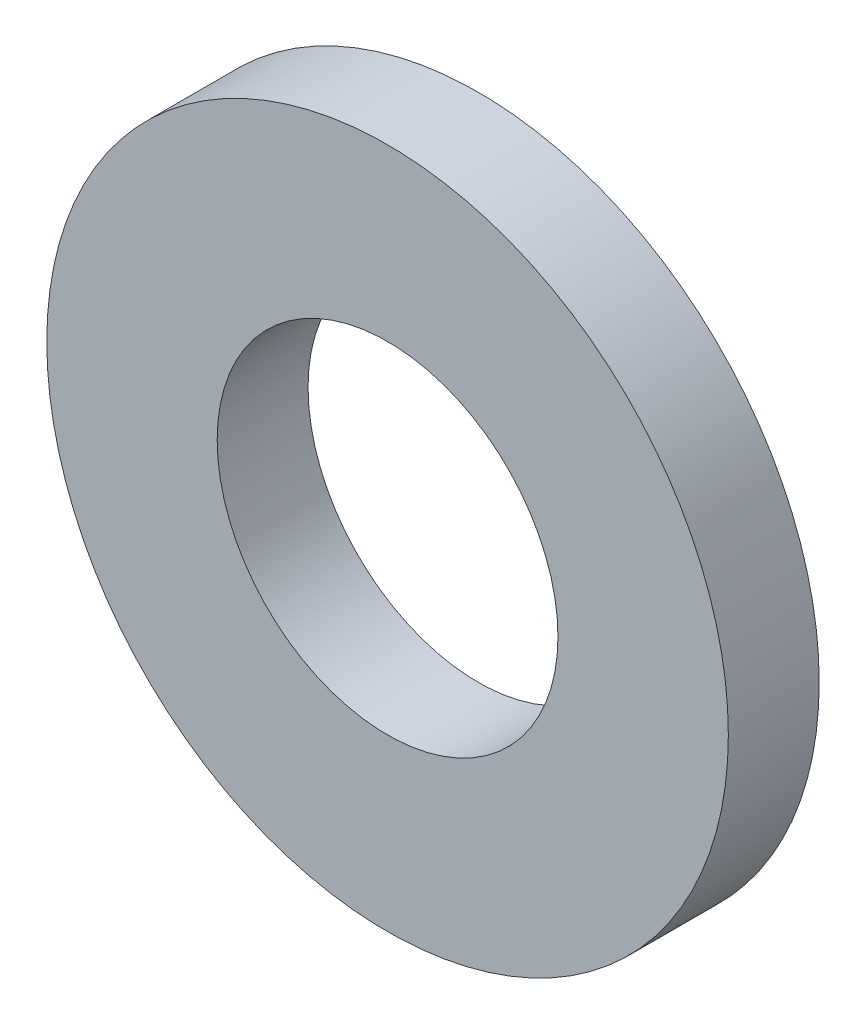
SolidWorks part; units mm, degrees
ref_plane "Face" through (0, 0, 0) normal (0, 0, 1) x (1, 0, 0)
ref_plane "Dessus" through (0, 0, 0) normal (0, 1, 0) x (1, 0, 0)
ref_plane "Droite" through (0, 0, 0) normal (1, 0, 0) x (0, 0, -1)
sketch "Esquisse1" plane through (0, 0, 0) normal (0, 0, 1) x (1, 0, 0)
  circle A0 centre (0, 0) radius 1.5
  circle A1 centre (0, 0) radius 3
extrude "Extrusion1" add sketch "Esquisse1" along normal blind 0.8
